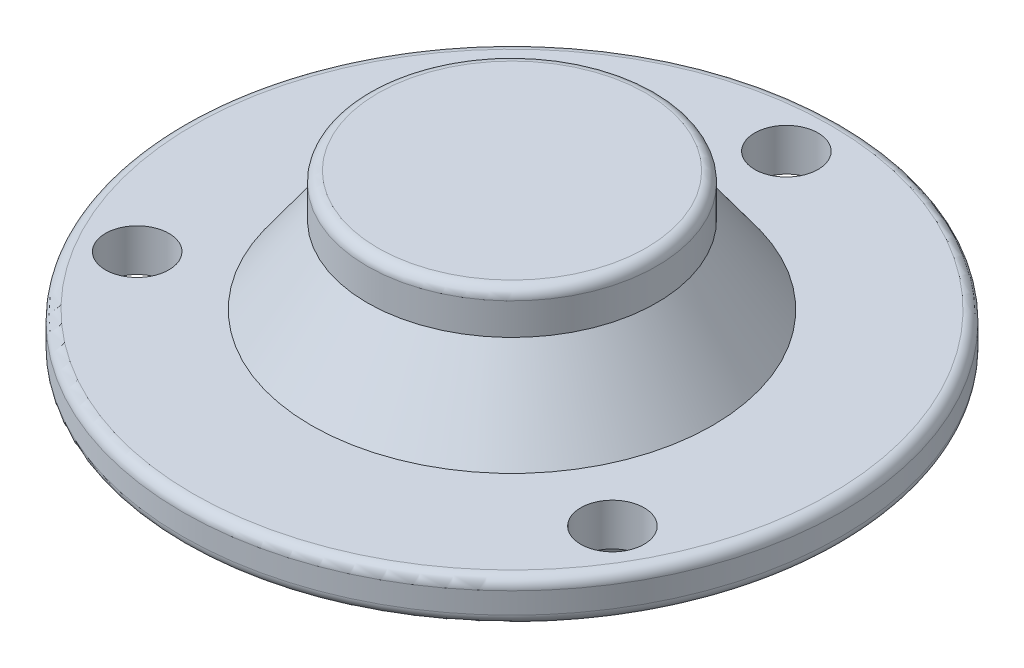
SolidWorks part; units mm, degrees
ref_plane "Plan de face" through (0, 0, 0) normal (0, 0, 1) x (1, 0, 0)
ref_plane "Plan de dessus" through (0, 0, 0) normal (0, 1, 0) x (1, 0, 0)
ref_plane "Plan de droite" through (0, 0, 0) normal (1, 0, 0) x (0, 0, -1)
sketch "Esquisse1" plane through (0, 0, 0) normal (0, 0, 1) x (1, 0, 0)
  line L0 (0, 5.7) -> (6.85, 5.7)
  line L1 (6.85, 5.7) -> (6.85, 3.7)
  line L2 (6.85, 3.7) -> (9.5, 0)
  line L3 (9.5, 0) -> (15.6, 0)
  line L4 (15.6, 0) -> (15.6, -2)
  line L5 (15.6, -2) -> (10, -2)
  line L6 (0, -25.6393) -> (0, 13.8917) construction
  line L7 (-11.2003, 0) -> (24.7755, 0) construction
  line L8 (0, 5.7) -> (0, -11.3)
  arc A0 (4.8803, -8.9545) -> (10, -2) centre (0, 0) ccw
  arc A1 (0, -11.3) -> (4.8803, -8.9545) centre (0, -5.05) ccw
  point P13 (0, -11.3)
  dimension "D9" = 12.5
  dimension "D1" = 17
  dimension "D2" = 13.7
  dimension "D3" = 2
  dimension "D4" = 19
  dimension "D5" = 31.2
  dimension "D6" = 2
  dimension "D7" = 20
  dimension "D8" = 7.7
revolve "Révolution1" add sketch "Esquisse1" angle 360 about L8
fillet "Congé1" radius 0.5 3 edges at (0, -2, 15.6) (0, 0, 15.6) (0, 5.7, 6.85)
sketch "Esquisse2" plane through (0, 0, 0) normal (0, 1, 0) x (1, 0, 0)
  line L1 (11.25, -6.4952) -> (0, 12.9904) construction
  line L2 (0, 12.9904) -> (-11.25, -6.4952) construction
  line L3 (-11.25, -6.4952) -> (11.25, -6.4952) construction
  circle A0 centre (0, 0) radius 6.4952 construction
  circle A1 centre (0, 12.9904) radius 1.5
  circle A2 centre (11.25, -6.4952) radius 1.5
  circle A3 centre (-11.25, -6.4952) radius 1.5
  point P9 (10.5, -5.1962)
  point P10 (0.75, 11.6913)
  dimension "D1" = 3
  dimension "D2" = 3
  dimension "D3" = 3
  dimension "D4" = 19.5
extrude "Enlèv. mat.-Extru.1" cut sketch "Esquisse2" against normal blind 10
ref_plane "Plan1" through (0, -11.3, 0) normal (0, -1, 0) x (-1, 0, 0)
